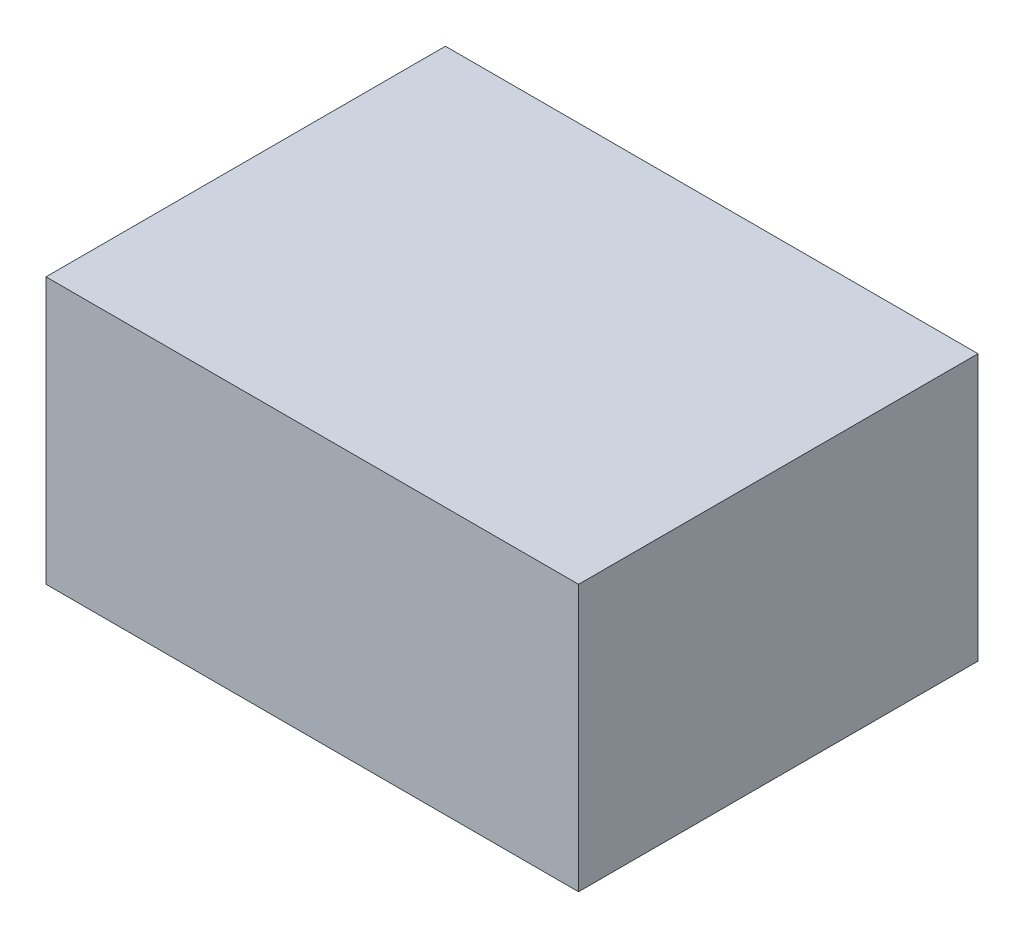
SolidWorks part; units mm, degrees
ref_plane "Front Plane" through (0, 0, 0) normal (0, 0, 1) x (1, 0, 0)
ref_plane "Top Plane" through (0, 0, 0) normal (0, 1, 0) x (1, 0, 0)
ref_plane "Right Plane" through (0, 0, 0) normal (1, 0, 0) x (0, 0, -1)
sketch "Sketch1" plane through (0, 0, 0) normal (0, 1, 0) x (1, 0, 0)
  line L1 (0, 0) -> (60, 0)
  line L2 (0, 0) -> (0, 45)
  line L3 (0, 45) -> (60, 45)
  line L4 (60, 0) -> (60, 45)
  dimension "D1" = 60
  dimension "D2" = 45
extrude "Boss-Extrude1" add sketch "Sketch1" along normal blind 30
